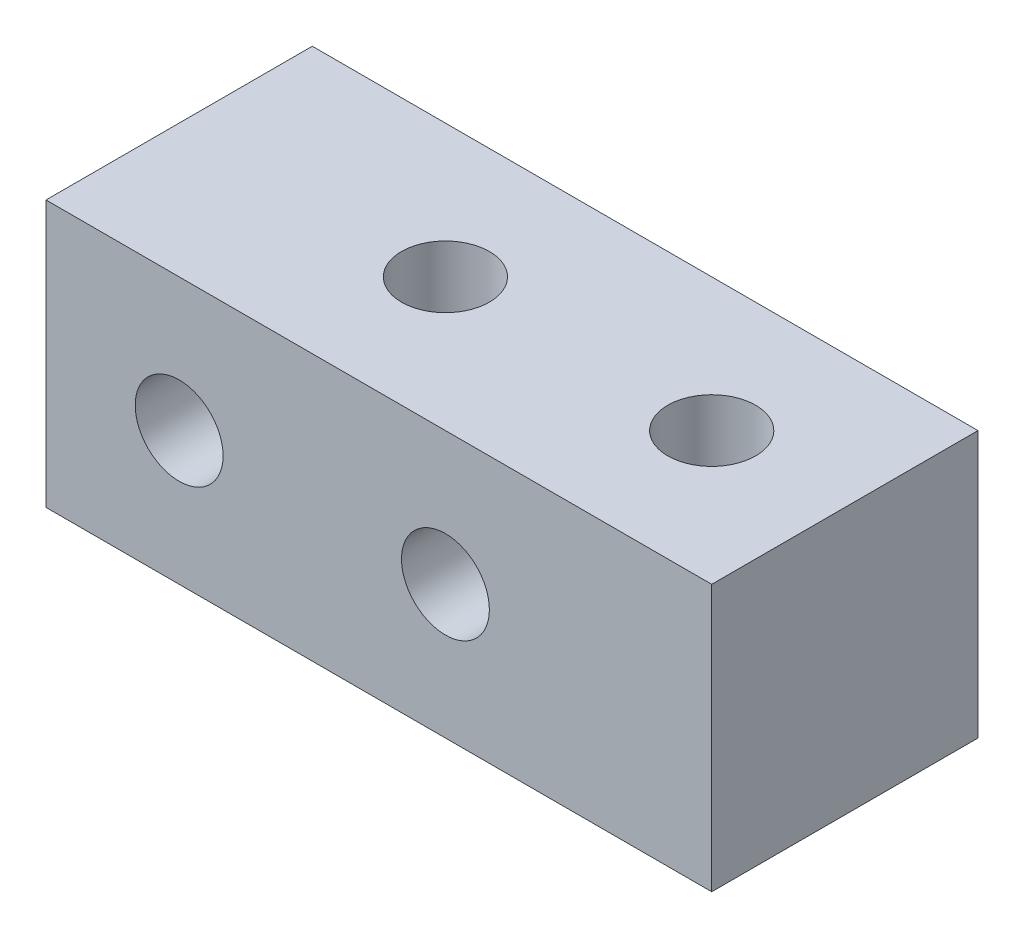
SolidWorks part; units mm, degrees
material "6061 合金"
ref_plane "前视基准面" through (0, 0, 0) normal (0, 0, 1) x (1, 0, 0)
ref_plane "上视基准面" through (0, 0, 0) normal (0, 1, 0) x (1, 0, 0)
ref_plane "右视基准面" through (0, 0, 0) normal (1, 0, 0) x (0, 0, -1)
sketch "草图1" plane through (0, 0, 0) normal (0, 0, 1) x (1, 0, 0)
  line L1 (12.5, -5) -> (-12.5, -5)
  line L2 (12.5, -5) -> (12.5, 5)
  line L3 (12.5, 5) -> (-12.5, 5)
  line L4 (-12.5, -5) -> (-12.5, 5)
  line L5 (12.5, -5) -> (-12.5, 5) construction
  line L6 (12.5, 5) -> (-12.5, -5) construction
  point P0 (0, 0)
  dimension "D1" = 25
  dimension "D2" = 10
extrude "凸台-拉伸1" add sketch "草图1" along normal blind 10
sketch "草图2" plane through (0, 0, 10) normal (0, 0, 1) x (1, 0, 0)
  line L0 (-12.5, 5) -> (-12.5, -5) construction
  point P0 (-7.5, 0)
  point P1 (2.5, 0)
  dimension "D1" = 5
  dimension "D2" = 10
sketch "草图3" plane through (0, 5, 0) normal (0, 1, 0) x (1, 0, 0)
  line L0 (12.5, -10) -> (12.5, 0) construction
  point P0 (7.5, -5)
  point P1 (-2.5, -5)
  dimension "D1" = 5
  dimension "D2" = 10
hole_wizard "M4 螺纹孔的螺纹孔钻头1" positions "3D草图1" profile "草图4" hole size "M4" standard "DIN" end condition through all
sketch3d "3D草图1"
  point P0 (-2.5, 5, 5)
  point P3 (7.5, 5, 5)
  point P6 (2.5, 0, 10)
  point P9 (-7.5, 0, 10)
  point P12 (-7.5, 0, 10)
sketch "草图4" plane through (-2.5, 5, 5) normal (1, 0, 0) x (0, 0, 1)
  line L0 (0, 0) -> (0, 10)
  line L1 (0, 10) -> (1.65, 10)
  line L2 (1.65, 10) -> (1.65, 0)
  line L5 (1.65, 0) -> (0, 0)
  line L11 (0, -6.35) -> (0, 107.95) construction
  dimension "通孔孔直径" = 3.3
  dimension "通孔孔深度" = 10
